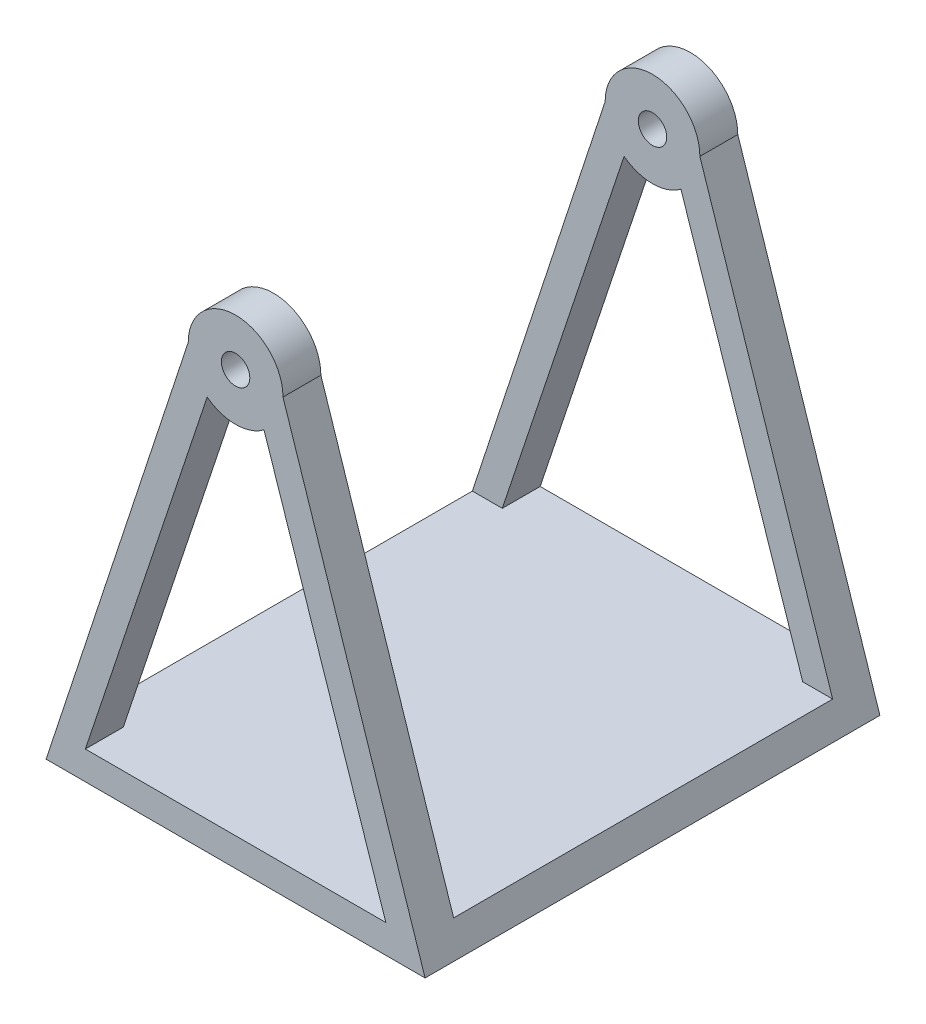
SolidWorks part; units mm, degrees
ref_plane "Front Plane" through (0, 0, 0) normal (0, 0, 1) x (1, 0, 0)
ref_plane "Top Plane" through (0, 0, 0) normal (0, 1, 0) x (1, 0, 0)
ref_plane "Right Plane" through (0, 0, 0) normal (1, 0, 0) x (0, 0, -1)
sketch "Sketch1" plane through (0, 0, 0) normal (0, 0, 1) x (1, 0, 0)
  line L0 (0, 0) -> (37.5, 0) construction
  line L1 (-187.7121, -100) -> (195.5682, -100) construction
  line L2 (-125, 0) -> (-500, -1139.9013)
  line L3 (-500, -1139.9013) -> (500, -1139.9013)
  line L4 (500, -1139.9013) -> (125, 0)
  line L5 (-75, -100) -> (-396.3726, -1064.9013)
  line L6 (-396.3726, -1064.9013) -> (396.3726, -1064.9013)
  line L7 (396.3726, -1064.9013) -> (75, -100)
  circle A0 centre (0, 0) radius 37.5
  circle A1 centre (0, 0) radius 125
  dimension "D1" = 75
  dimension "D2" = 250
  dimension "D3" = 75
  dimension "D4" = 1200
  dimension "D5" = 75
  dimension "D6" = 1000
  dimension "D7" = 100
extrude "Boss-Extrude1" add sketch "Sketch1" along normal blind 100 contours A1 L2 L3 L4 L7 L6 L5 | A1 A0
ref_plane "Plane1" through (0, 0, 600) normal (0, 0, 1) x (1, 0, 0)
sketch "Sketch3" plane through (0, 0, 100) normal (0, 0, 1) x (1, 0, 0)
  line L0 (-500, -1139.9013) -> (-475.3268, -1064.9013)
  line L1 (-125, 0) -> (-500, -1139.9013) construction
  line L2 (-475.3268, -1064.9013) -> (475.3268, -1064.9013)
  line L3 (500, -1139.9013) -> (125, 0) construction
  line L4 (475.3268, -1064.9013) -> (500, -1139.9013)
  line L5 (500, -1139.9013) -> (-500, -1139.9013)
extrude "Boss-Extrude3" add sketch "Sketch3" along normal blind 500
mirror "Mirror2" about plane through (0, 0, 600) normal (0, 0, 1) of bodies 104
